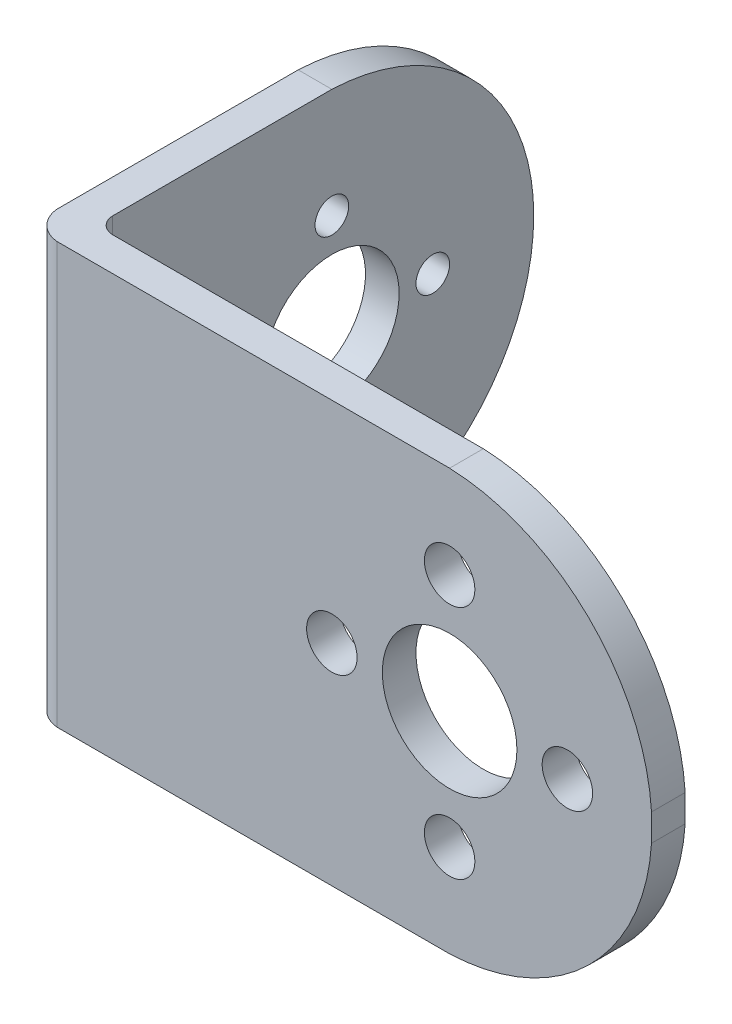
SolidWorks part; units mm, degrees
material "1060 Alloy"
ref_plane "Front Plane" through (0, 0, 0) normal (0, 0, 1) x (1, 0, 0)
ref_plane "Top Plane" through (0, 0, 0) normal (0, 1, 0) x (1, 0, 0)
ref_plane "Right Plane" through (0, 0, 0) normal (1, 0, 0) x (0, 0, -1)
sketch "Sketch1" plane through (0, 0, 0) normal (0, 1, 0) x (1, 0, 0)
  line L0 (1.6591, 0) -> (37, 0)
  line L1 (37, 0) -> (37, 2)
  line L2 (37, 2) -> (2.9676, 2)
  line L3 (0, 2) -> (0, 1.6591)
  line L4 (0, 1.6591) -> (0, 28)
  line L5 (0, 28) -> (2, 28)
  line L6 (2, 28) -> (2, 2.9676)
  arc A0 (0, 2) -> (2, 0) centre (1.8295, 1.8295) ccw
  arc A1 (2, 2.9676) -> (3.0387, 2) centre (3.0031, 3.0031) ccw
  dimension "D1" = 2
extrude "Boss-Extrude1" add sketch "Sketch1" along normal blind 25 contours A1 L6 L5 L4 L3 A0 L0 L1 L2
sketch "Sketch2" plane through (0, 0, 0) normal (-1, 0, 0) x (0, 0, 1)
  line L0 (-28, 12.5) -> (-16, 12.5) construction
  line L1 (-28, 25) -> (-28, 0) construction
  line L2 (-1.6591, 0) -> (-28, 0) construction
  line L3 (-1.6591, 25) -> (-28, 25) construction
  line L4 (-16, 25) -> (-28, 25)
  line L5 (-28, 25) -> (-28, 12.5)
  line L6 (-28, 12.5) -> (-28, 0)
  line L7 (-28, 0) -> (-16, 0)
  arc A0 (-16, 0) -> (-16, 25) centre (-15.4896, 12.5) cw
  line M3 (-28, 0) -> (-1.6591, 0)
  line M5 (-1.6591, 25) -> (-28, 25)
  line M6 (-28, 25) -> (-28, 0)
  dimension "D1" = 12
extrude "Cut-Extrude1" cut sketch "Sketch2" against normal blind 25 contours A0 M6 M5 | A0 M3 M6
sketch "Sketch4" plane through (0, 0, 0) normal (0, 0, 1) x (1, 0, 0)
  line L0 (37, 12.5) -> (25, 12.5) construction
  line L1 (37, 25) -> (37, 0) construction
  line L2 (1.6591, 0) -> (37, 0) construction
  line L3 (1.6591, 25) -> (37, 25) construction
  line L4 (25, 25) -> (37, 25)
  line L5 (37, 25) -> (37, 12.5)
  line L6 (37, 12.5) -> (37, 0)
  line L7 (37, 0) -> (25, 0)
  line L8 (25, 12.5) -> (25, 19.5) construction
  circle A0 centre (25, 12.5) radius 4
  arc A1 (25, 0) -> (25, 25) centre (24.5166, 12.5) ccw
  circle A2 centre (25, 19.5) radius 1.5
  circle A3 centre (32, 12.5) radius 1.5
  circle A4 centre (25, 5.5) radius 1.5
  circle A5 centre (18, 12.5) radius 1.5
  point P27 (25, 12.5)
  line M1 (1.6591, 0) -> (37, 0)
  line M2 (37, 0) -> (37, 25)
  line M3 (37, 25) -> (1.6591, 25)
  dimension "D1" = 3
  dimension "D2" = 4
extrude "Cut-Extrude2" cut sketch "Sketch4" against normal blind 25 contours A1 L5 M3 | A1 M1 M2
sketch "Sketch5" plane through (0, 0, 0) normal (0, 0, 1) x (1, 0, 0)
  line L0 (37, 12.5) -> (25, 12.5) construction
  line L1 (37, 13.3055) -> (37, 11.6945) construction
  line L2 (25, 12.5) -> (25, 19.5) construction
  circle A0 centre (25, 12.5) radius 4
  circle A5 centre (25, 19.5) radius 1.5
  circle A6 centre (32, 12.5) radius 1.5
  circle A7 centre (25, 5.5) radius 1.5
  circle A8 centre (18, 12.5) radius 1.5
  point P16 (25, 12.5)
  point P17 (25, 12.5)
  dimension "D1" = 7
  dimension "D2" = 4
extrude "Cut-Extrude3" cut sketch "Sketch5" against normal blind 25
sketch "Sketch6" plane through (0, 0, 0) normal (-1, 0, 0) x (0, 0, 1)
  line L0 (-28, 12.5) -> (-16, 12.5) construction
  line L1 (-16, 12.5) -> (-16, 5.5) construction
  arc A0 (-16, 25) -> (-16, 0) centre (-15.4896, 12.5) ccw construction
  circle A1 centre (-16, 12.5) radius 4
  circle A6 centre (-16, 12.5) radius 6 construction
  circle A7 centre (-16, 18.5) radius 1
  circle A10 centre (-10, 12.5) radius 1
  circle A11 centre (-16, 6.5) radius 1
  circle A12 centre (-22, 12.5) radius 1
  point P18 (-16, 12.5)
  point P25 (-16, 12.5)
  dimension "D1" = 7
  dimension "D2" = 4
  dimension "D3" = 12
  dimension "D4" = 2
extrude "Cut-Extrude4" cut sketch "Sketch6" against normal blind 25
